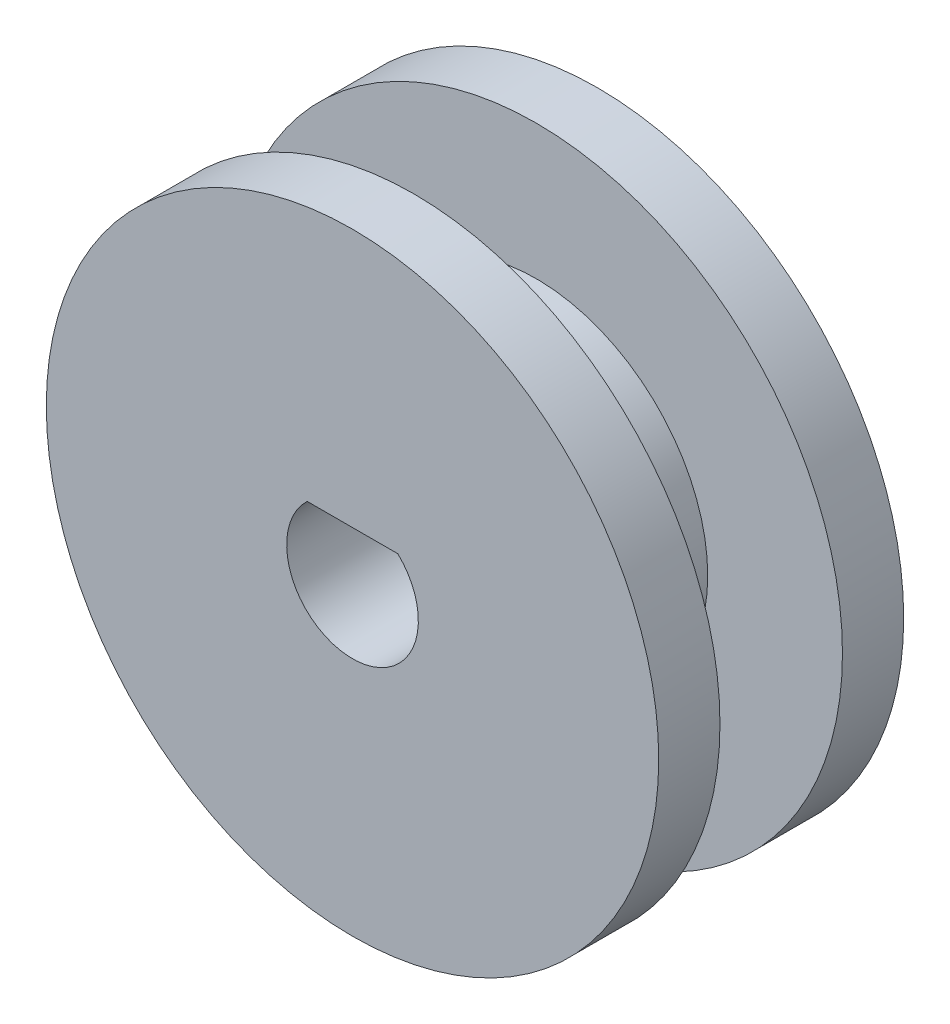
SolidWorks part; units mm, degrees
ref_plane "Front Plane" through (0, 0, 0) normal (0, 0, 1) x (1, 0, 0)
ref_plane "Top Plane" through (0, 0, 0) normal (0, 1, 0) x (1, 0, 0)
ref_plane "Right Plane" through (0, 0, 0) normal (1, 0, 0) x (0, 0, -1)
sketch "Sketch1" plane through (0, 0, 0) normal (0, 0, 1) x (1, 0, 0)
  circle A0 centre (0, 0) radius 10
  dimension "D1" = 20
extrude "Boss-Extrude1" add sketch "Sketch1" along normal blind 2
sketch "Sketch2" plane through (0, 0, 2) normal (0, 0, 1) x (1, 0, 0)
  circle A0 centre (0, 0) radius 5.6
  dimension "D1" = 11.2
extrude "Boss-Extrude2" add sketch "Sketch2" along normal blind 4
sketch "Sketch3" plane through (0, 0, 6) normal (0, 0, 1) x (1, 0, 0)
  circle A0 centre (0, 0) radius 10
  dimension "D1" = 20
extrude "Boss-Extrude3" add sketch "Sketch3" along normal blind 2
sketch "Sketch6" plane through (0, 0, 8) normal (0, 0, 1) x (1, 0, 0)
  line L1 (-2.8577, 3.5542) -> (3.2144, 3.5542)
  line L2 (-2.8577, 3.5542) -> (-2.8577, 1.56)
  line L3 (-2.8577, 1.56) -> (3.2144, 1.56)
  line L4 (3.2144, 3.5542) -> (3.2144, 1.56)
  circle A0 centre (0, 0) radius 2.15
  dimension "D1" = 4.3
  dimension "D2" = 1.56
extrude "Cut-Extrude1" cut sketch "Sketch6" against normal through all contours L3 A0
